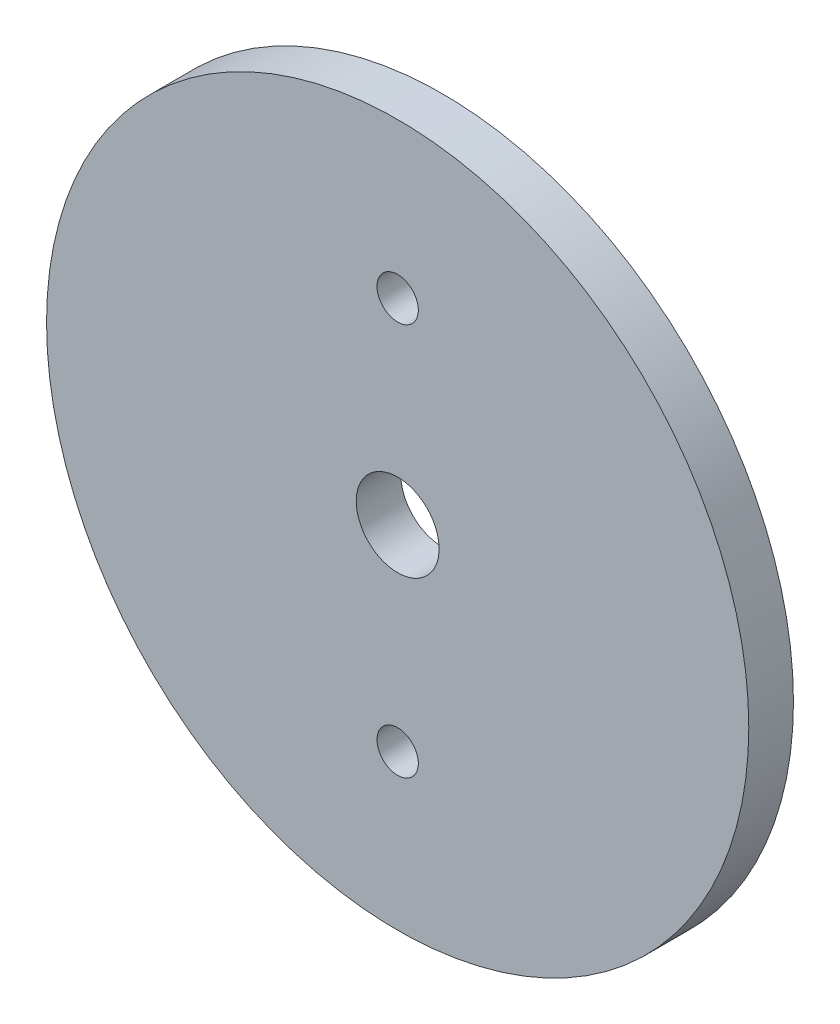
SolidWorks part; units mm, degrees
ref_plane "Front Plane" through (0, 0, 0) normal (0, 0, 1) x (1, 0, 0)
ref_plane "Top Plane" through (0, 0, 0) normal (0, 1, 0) x (1, 0, 0)
ref_plane "Right Plane" through (0, 0, 0) normal (1, 0, 0) x (0, 0, -1)
sketch "Sketch1" plane through (0, 0, 0) normal (0, 0, 1) x (1, 0, 0)
  line L0 (0, 25) -> (0, 2.95) construction
  line L1 (0, -2.95) -> (0, -25) construction
  circle A0 centre (0, 0) radius 2.95
  circle A1 centre (0, 0) radius 25
  circle A2 centre (0, 13.975) radius 1.47
  circle A3 centre (0, -13.975) radius 1.47
  dimension "D1" = 5.9
  dimension "D2" = 50
  dimension "D3" = 2.94
  dimension "D4" = 2.94
extrude "Boss-Extrude1" add sketch "Sketch1" along normal blind 3.18
